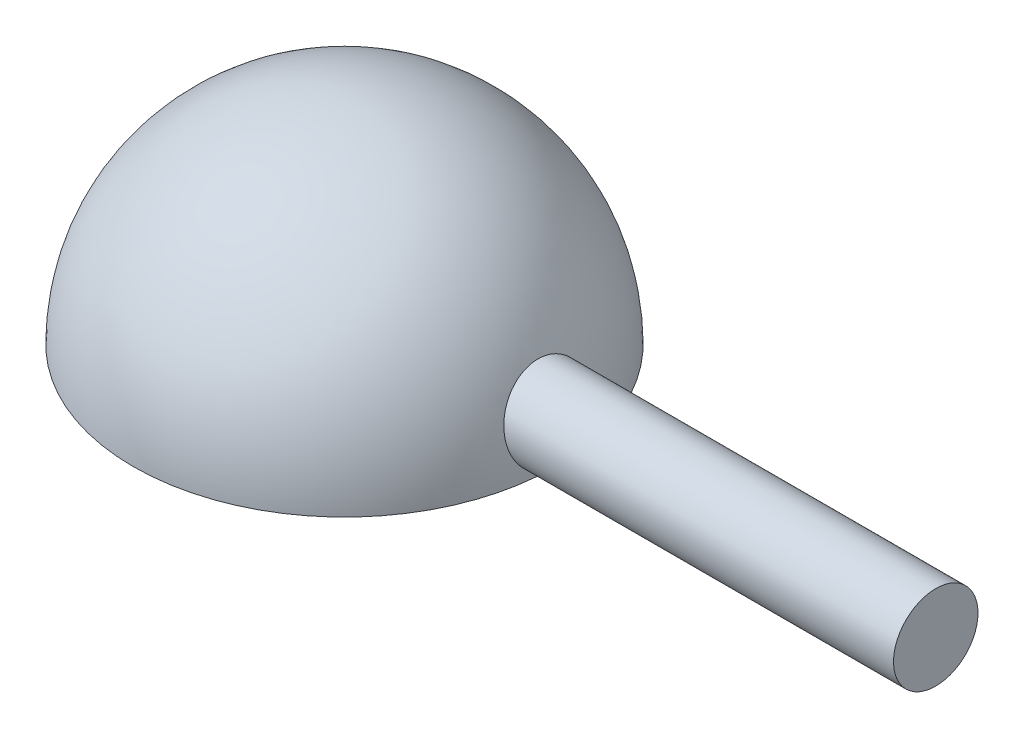
SolidWorks part; units mm, degrees
ref_plane "Front Plane" through (0, 0, 0) normal (0, 0, 1) x (1, 0, 0)
ref_plane "Top Plane" through (0, 0, 0) normal (0, 1, 0) x (1, 0, 0)
ref_plane "Right Plane" through (0, 0, 0) normal (1, 0, 0) x (0, 0, -1)
sketch "boog" plane through (0, 0, 0) normal (0, 0, 1) x (1, 0, 0)
  line L0 (-25, 0) -> (-22, 0)
  line L2 (0, 0) -> (0, 22) construction
  line L3 (0, 22) -> (0, 25)
  arc A0 (0, 22) -> (-22, 0) centre (0, 0) ccw
  arc A1 (0, 25) -> (-25, 0) centre (0, 0) ccw
  dimension "D1" = 3
  dimension "D2" = 25
revolve "bol" add sketch "boog" angle 360 about L2
ref_plane "Plane1" through (25, 0, 0) normal (1, 0, 0) x (0, 0, -1)
sketch "cirkel" plane through (25, 0, 0) normal (1, 0, 0) x (0, 0, -1)
  line L0 (-25, 0) -> (25, 0) construction
  line L1 (0, 0) -> (0, 5) construction
  circle A0 centre (0, 5) radius 5
  dimension "D1" = 10
extrude "arm" add sketch "cirkel" along normal blind 45 and the other way up to next
